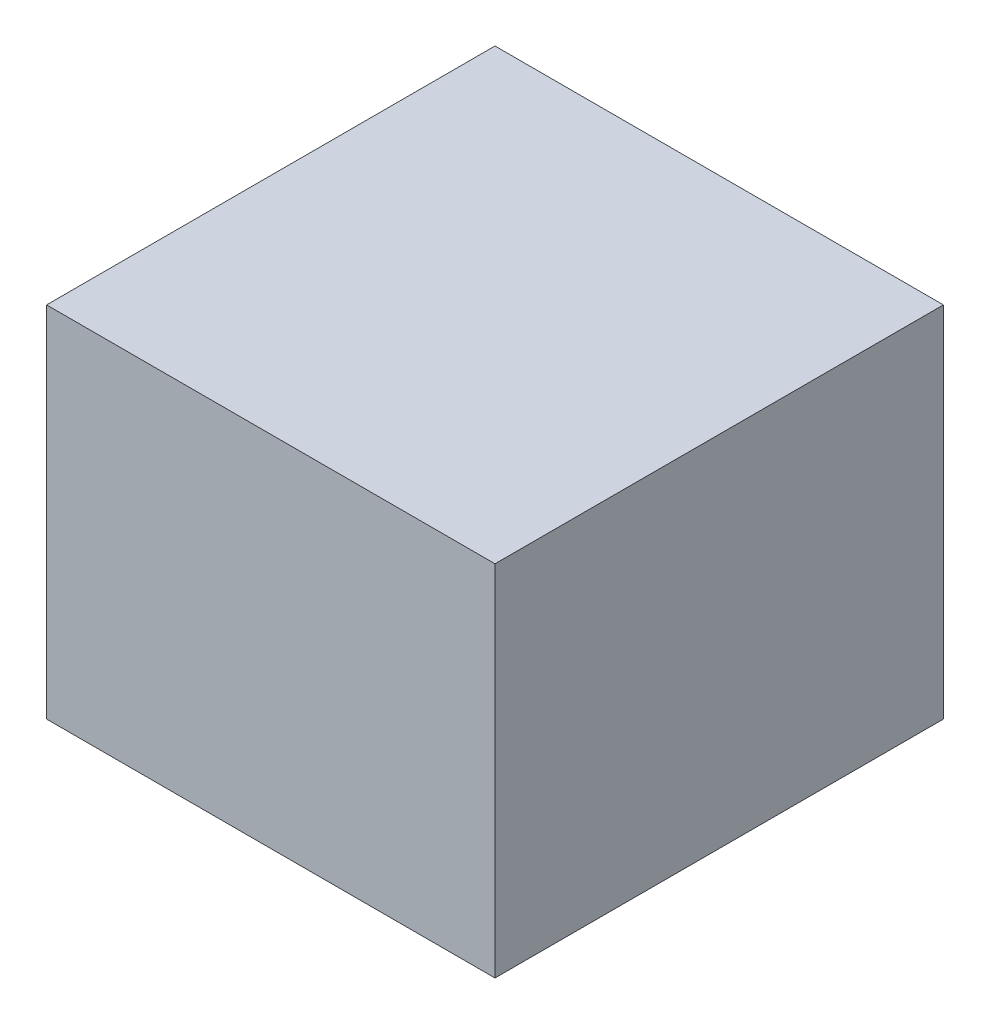
SolidWorks part; units mm, degrees
ref_plane "Front Plane" through (0, 0, 0) normal (0, 0, 1) x (1, 0, 0)
ref_plane "Top Plane" through (0, 0, 0) normal (0, 1, 0) x (1, 0, 0)
ref_plane "Right Plane" through (0, 0, 0) normal (1, 0, 0) x (0, 0, -1)
sketch "Sketch1" plane through (0, 0, 0) normal (0, 1, 0) x (1, 0, 0)
  line L1 (-8.75, -8.75) -> (8.75, -8.75)
  line L2 (-8.75, -8.75) -> (-8.75, 8.75)
  line L3 (-8.75, 8.75) -> (8.75, 8.75)
  line L4 (8.75, -8.75) -> (8.75, 8.75)
  line L5 (-8.75, -8.75) -> (8.75, 8.75) construction
  line L6 (-8.75, 8.75) -> (8.75, -8.75) construction
  point P0 (0, 0)
  dimension "D1" = 17.5
extrude "Boss-Extrude1" add sketch "Sketch1" along normal blind 14
